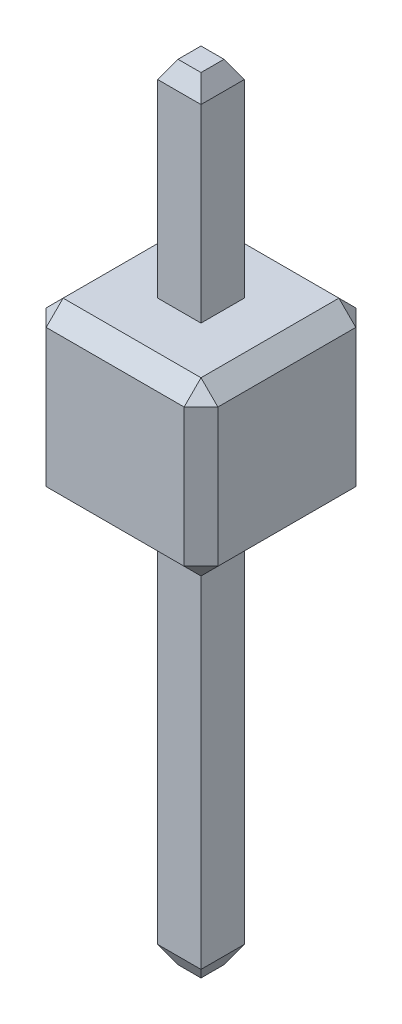
SolidWorks part; units mm, degrees
ref_plane "Plano frontal" through (0, 0, 0) normal (0, 0, 1) x (1, 0, 0)
ref_plane "Plano superior" through (0, 0, 0) normal (0, 1, 0) x (1, 0, 0)
ref_plane "Plano direito" through (0, 0, 0) normal (1, 0, 0) x (0, 0, -1)
sketch "Esboço1" plane through (0, 0, 0) normal (0, 0, 1) x (1, 0, 0)
  line L1 (-0.32, 5.8) -> (0.32, 5.8)
  line L2 (-0.32, 5.8) -> (-0.32, -5.8)
  line L3 (-0.32, -5.8) -> (0.32, -5.8)
  line L4 (0.32, 5.8) -> (0.32, -5.8)
  line L5 (-0.32, 5.8) -> (0.32, -5.8) construction
  line L6 (-0.32, -5.8) -> (0.32, 5.8) construction
  point P0 (0, 0)
  dimension "D1" = 0.64
  dimension "D2" = 11.6
extrude "Ressalto-extrusão1" add sketch "Esboço1" along normal mid plane 0.64
sketch "Esboço2" plane through (0, 0, 0) normal (0, 0, 1) x (1, 0, 0)
  line L0 (0.32, 5.8) -> (-0.32, 5.8) construction
  line L1 (1.27, 2.74) -> (-1.27, 2.74)
  line L2 (1.27, 2.74) -> (1.27, 0.2)
  line L3 (1.27, 0.2) -> (-1.27, 0.2)
  line L4 (-1.27, 2.74) -> (-1.27, 0.2)
  line L5 (1.27, 2.74) -> (-1.27, 0.2) construction
  line L6 (1.27, 0.2) -> (-1.27, 2.74) construction
  line L7 (0, 0) -> (0, 5.8) construction
  point P0 (0, 1.47)
  point P10 (0, 0)
  dimension "D1" = 3.06
  dimension "D2" = 2.54
  dimension "D3" = 2.54
extrude "Ressalto-extrusão2" add sketch "Esboço2" along normal mid plane 2.54
chamfer "Chanfro1" distance 0.15 distance2 0.26 4 edges at (0, 5.8, -0.32) (0.32, 5.8, 0) (0, 5.8, 0.32) (-0.32, 5.8, 0)
chamfer "Chanfro2" distance 0.26 distance2 0.15 4 edges at (0, -5.8, 0.32) (0.32, -5.8, 0) (0, -5.8, -0.32) (-0.32, -5.8, 0)
chamfer "Chanfro3" distance 0.25 angle 45 12 edges at (-1.27, 2.74, 0) (0, 2.74, 1.27) (1.27, 2.74, 0) (0, 2.74, -1.27) (1.27, 0.2, 0) (1.27, 1.47, 1.27) (0, 0.2, 1.27) (-1.27, 1.47, 1.27) (-1.27, 0.2, 0) (1.27, 1.47, -1.27) (0, 0.2, -1.27) (-1.27, 1.47, -1.27)
